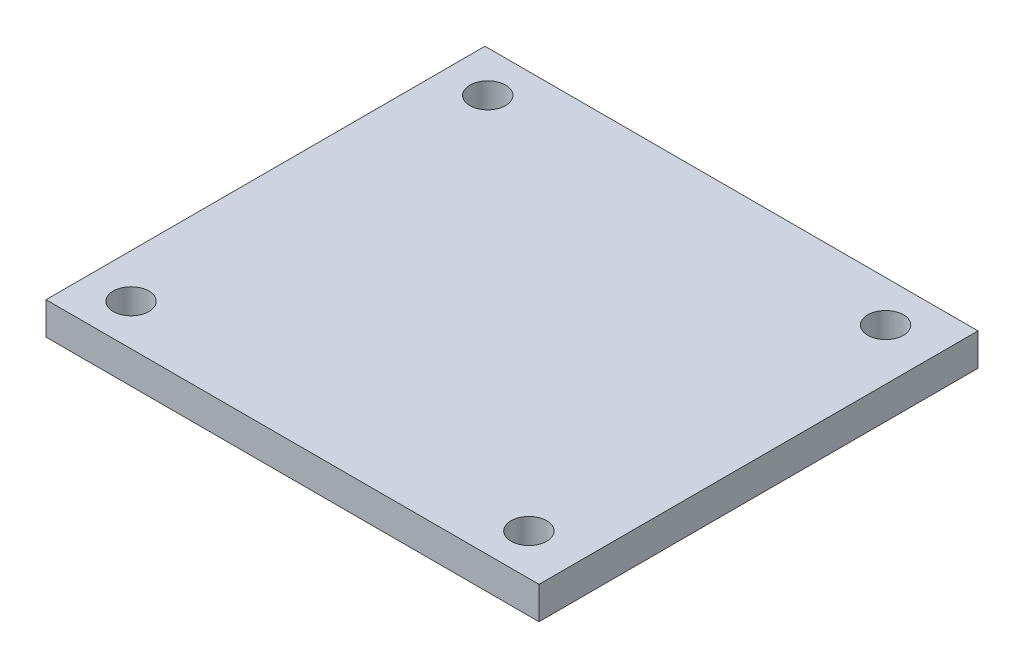
SolidWorks part; units mm, degrees
ref_plane "Front Plane" through (0, 0, 0) normal (0, 0, 1) x (1, 0, 0)
ref_plane "Top Plane" through (0, 0, 0) normal (0, 1, 0) x (1, 0, 0)
ref_plane "Right Plane" through (0, 0, 0) normal (1, 0, 0) x (0, 0, -1)
sketch "Sketch1" plane through (0, 0, 0) normal (0, 1, 0) x (1, 0, 0)
  line L1 (-22.82, 20.32) -> (0, 20.32)
  line L2 (-22.82, 20.32) -> (-22.82, 0)
  line L3 (-22.82, 0) -> (0, 0)
  line L4 (0, 20.32) -> (0, 0)
  dimension "D1" = 22.82
  dimension "D2" = 20.32
extrude "Boss-Extrude1" add sketch "Sketch1" along normal blind 1.5 contours L1 L4 L3 L2
sketch "Sketch2" plane through (0, 1.5, 0) normal (0, 1, 0) x (1, 0, 0)
  line L0 (-22.82, 20.32) -> (-22.82, 0) construction
  line L1 (-22.82, 20.32) -> (0, 20.32) construction
  circle A0 centre (-2.373, 18.415) radius 0.825
  circle A1 centre (-20.788, 18.415) radius 0.825
  circle A2 centre (-20.788, 1.905) radius 0.825
  circle A3 centre (-2.373, 1.905) radius 0.825
  point P10 (0, 0)
  dimension "D1" = 1.65
  dimension "D2" = 1.65
  dimension "D3" = 1.65
  dimension "D4" = 1.65
  dimension "D5" = 18.415
  dimension "D6" = 16.51
  dimension "D7" = 18.415
  dimension "D8" = 16.51
  dimension "D9" = 16.51
  dimension "D10" = 2.032
  dimension "D11" = 1.905
  dimension "D12" = 2.032
extrude "Cut-Extrude1" cut sketch "Sketch2" against normal through all contours A2 | A3 | A0 | A1
